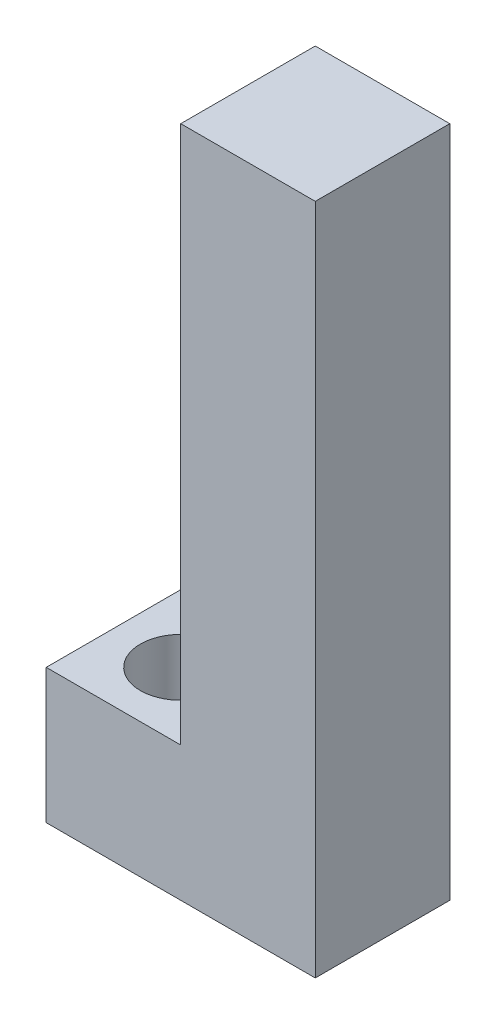
SolidWorks part; units mm, degrees
ref_plane "Front Plane" through (0, 0, 0) normal (0, 0, 1) x (1, 0, 0)
ref_plane "Top Plane" through (0, 0, 0) normal (0, 1, 0) x (1, 0, 0)
ref_plane "Right Plane" through (0, 0, 0) normal (1, 0, 0) x (0, 0, -1)
sketch "Sketch1" plane through (0, 0, 0) normal (0, 0, 1) x (1, 0, 0)
  line L4 (0, 0) -> (5, 0)
  line L5 (5, 0) -> (5, 20)
  line L6 (5, 20) -> (10, 20)
  line L7 (10, 20) -> (10, -5)
  line L8 (10, -5) -> (0, -5)
  line L9 (0, -5) -> (0, 0)
  dimension "D1" = 25
  dimension "D2" = 5
  dimension "D3" = 5
  dimension "D4" = 10
extrude "Boss-Extrude1" add sketch "Sketch1" along normal blind 5
sketch "Sketch2" plane through (0, 0, 0) normal (0, 1, 0) x (1, 0, 0)
  line L0 (0, -2.5) -> (5, -2.5) construction
  line L1 (0, -5) -> (0, 0) construction
  line L2 (5, -5) -> (5, 0) construction
  circle A0 centre (2.5, -2.5) radius 1.5
extrude "Cut-Extrude1" cut sketch "Sketch2" against normal through all
